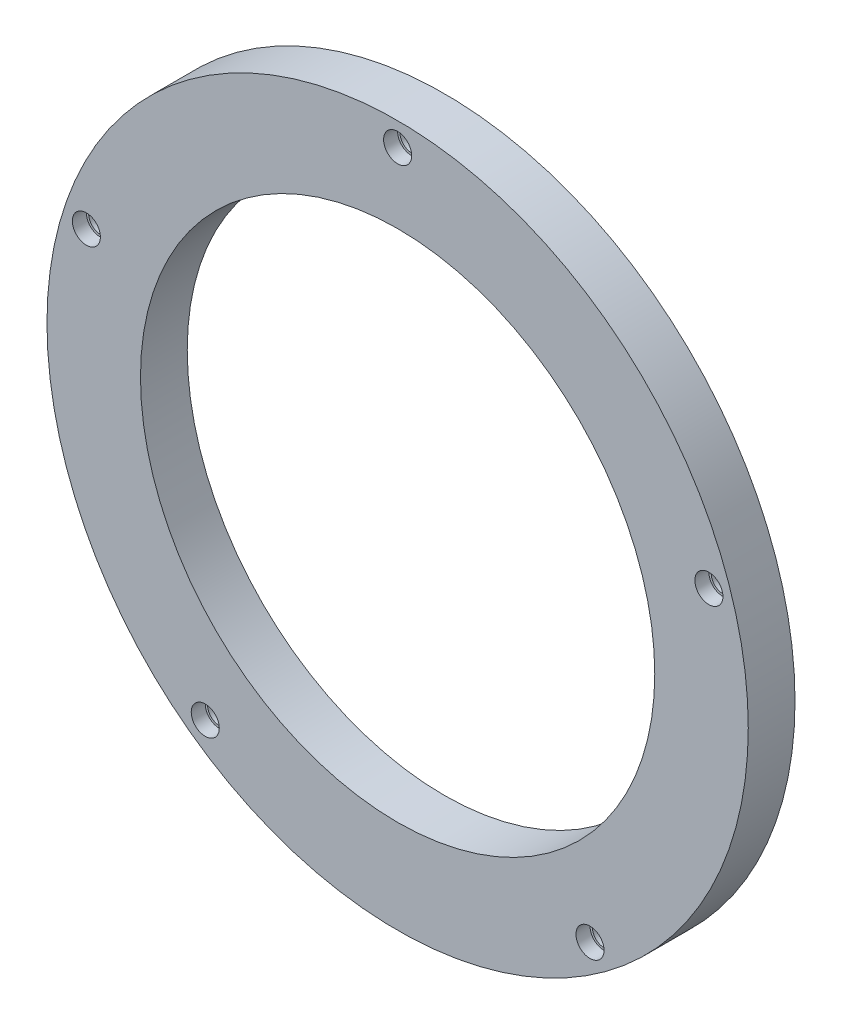
SolidWorks part; units mm, degrees
ref_plane "Front Plane" through (0, 0, 0) normal (1, 0, 0) x (0, 1, 0)
ref_plane "Top Plane" through (0, 0, 0) normal (0, 0, 1) x (0, 1, 0)
ref_plane "Right Plane" through (0, 0, 0) normal (0, 1, 0) x (-1, 0, 0)
sketch "Sketch2" plane through (0, 0, 0) normal (0, 0, 1) x (0, 1, 0)
  circle A0 centre (0, 0) radius 75
  dimension "D1" = 150
extrude "Boss-Extrude1" add sketch "Sketch2" along normal blind 10
sketch "Sketch3" plane through (0, 0, 10) normal (0, 0, 1) x (1, 0, 0)
  circle A0 centre (0, 0) radius 55
  dimension "D1" = 110
extrude "Cut-Extrude1" cut sketch "Sketch3" against normal blind 10
sketch "Sketch5" plane through (0, 0, 10) normal (0, 0, 1) x (1, 0, 0)
  circle A1 centre (0, 70) radius 2.5
  dimension "D2" = 5
sketch "Sketch6" plane through (0, 0, 10) normal (0, 0, 1) x (1, 0, 0)
  circle A0 centre (0, 70) radius 3
  dimension "D1" = 6
extrude "Cut-Extrude2" cut sketch "Sketch6" against normal blind 3 contours A0
extrude "Cut-Extrude3" cut sketch "Sketch5" against normal through all contours A1
pattern_circular "CirPattern2" count 5 over 360 about axis through (0, 0, 0) along (0, 0, 1) of "Cut-Extrude3", "Cut-Extrude2"
